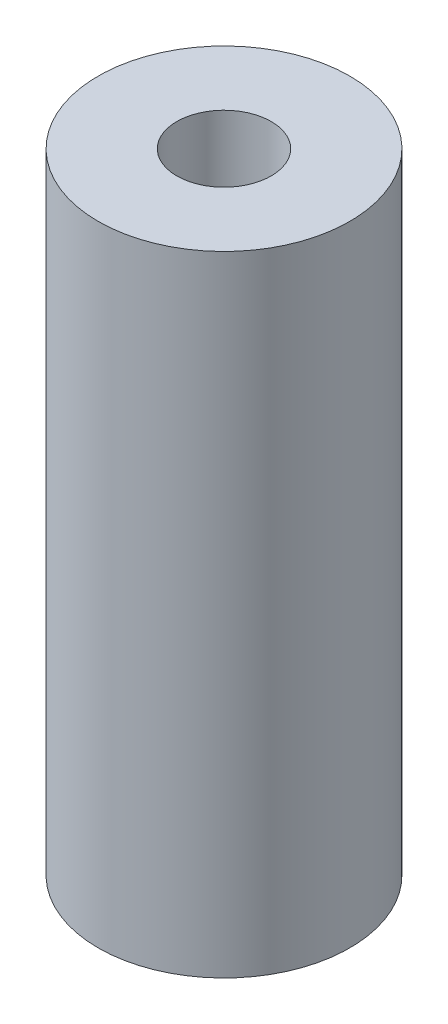
SolidWorks part; units mm, degrees
ref_plane "Plan de face" through (0, 0, 0) normal (0, 0, 1) x (1, 0, 0)
ref_plane "Plan de dessus" through (0, 0, 0) normal (0, 1, 0) x (1, 0, 0)
ref_plane "Plan de droite" through (0, 0, 0) normal (1, 0, 0) x (0, 0, -1)
sketch "Esquisse1" plane through (0, 0, 0) normal (0, 1, 0) x (1, 0, 0)
  circle A0 centre (0, 0) radius 2
  circle A1 centre (0, 0) radius 0.75
  dimension "D1" = 1.5
  dimension "D2" = 4
extrude "Boss.-Extru.1" add sketch "Esquisse1" along normal blind 10
